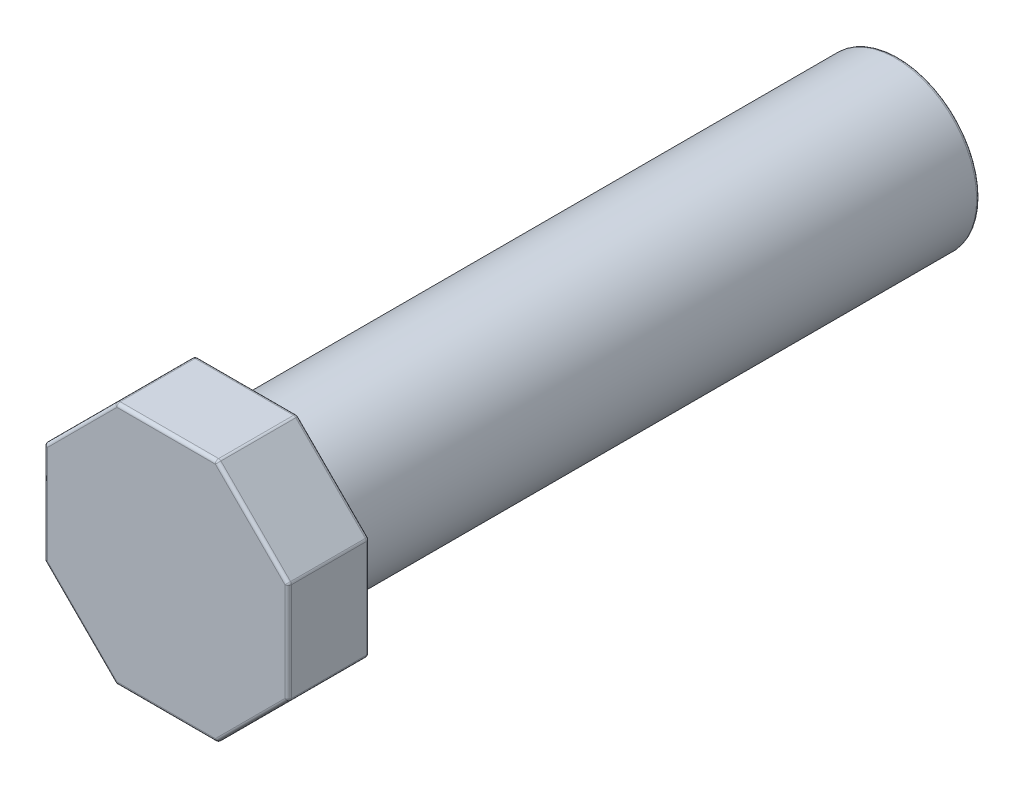
SolidWorks part; units mm, degrees
material "AISI 1020"
ref_plane "Front Plane" through (0, 0, 0) normal (0, 0, 1) x (1, 0, 0)
ref_plane "Top Plane" through (0, 0, 0) normal (0, 1, 0) x (1, 0, 0)
ref_plane "Right Plane" through (0, 0, 0) normal (1, 0, 0) x (0, 0, -1)
sketch "Sketch1" plane through (0, 0, 0) normal (0, 0, 1) x (1, 0, 0)
  circle A0 centre (0, 0) radius 6.35
  dimension "D1" = 12.7
extrude "Boss-Extrude1" add sketch "Sketch1" along normal blind 50.8
cosmetic thread "Cosmetic Thread1" parameters "D2"=5.268
sketch "Sketch2" plane through (0, 0, 50.8) normal (0, 0, 1) x (1, 0, 0)
  line L5 (-3.9454, 9.525) -> (-9.525, 3.9454)
  line L6 (3.9454, 9.525) -> (-3.9454, 9.525)
  line L10 (9.525, 3.9454) -> (9.525, -3.9454)
  line L11 (3.9454, -9.525) -> (-3.9454, -9.525)
  line L12 (-9.525, 3.9454) -> (-9.525, -3.9454)
  line L13 (6.7352, 6.7352) -> (-6.7352, -6.7352) construction
  line L14 (6.7352, -6.7352) -> (-6.7352, 6.7352) construction
  line L15 (3.9454, 9.525) -> (9.525, 3.9454)
  line L16 (9.525, -3.9454) -> (3.9454, -9.525)
  line L17 (-9.525, -3.9454) -> (-3.9454, -9.525)
  line L18 (0, 9.525) -> (0, -9.525) construction
  line L19 (9.525, 0) -> (-9.525, 0) construction
  point P0 (0, 0)
  point P1 (0, 0)
extrude "Boss-Extrude3" add sketch "Sketch2" along normal blind 6.35
ref_plane "Plane1" through (0, 0, -102.4) normal (0, 0, -1) x (-1, 0, 0)
ref_plane "Plane2" through (0, 0, 50.8) normal (0, 0, -1) x (-1, 0, 0)
split "Split1" trim tools "Plane2" bodies to split 103 resulting bodies 104 105
fillet "Fillet1" radius 0.254 24 edges at (3.9454, -9.525, 53.975) (9.525, -3.9454, 53.975) (0, -9.525, 50.8) (6.7352, -6.7352, 50.8) (9.525, 0, 50.8) (9.525, 0, 57.15) (6.7352, -6.7352, 57.15) (0, -9.525, 57.15) (-6.7352, -6.7352, 57.15) (-3.9454, -9.525, 53.975) (-6.7352, -6.7352, 50.8) (-9.525, 0, 57.15) (-9.525, -3.9454, 53.975) (-9.525, 0, 50.8) (0, 9.525, 57.15) (0, 9.525, 50.8) (-3.9454, 9.525, 53.975) (-6.7352, 6.7352, 57.15) (-9.525, 3.9454, 53.975) (-6.7352, 6.7352, 50.8) (9.525, 3.9454, 53.975) (6.7352, 6.7352, 57.15) (3.9454, 9.525, 53.975) (6.7352, 6.7352, 50.8)
fillet "Fillet2" radius 0.254 1 edges at (6.35, 0, 0)
split "Split2" trim tools "Plane2" bodies to split 104 resulting bodies 106
